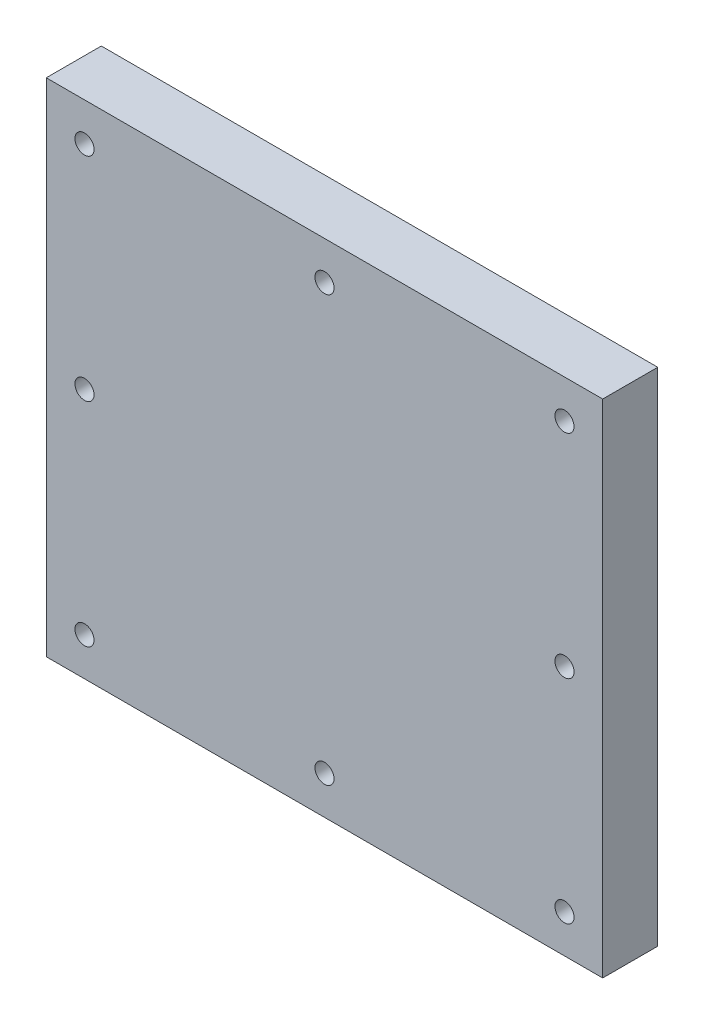
SolidWorks part; units mm, degrees
ref_plane "Front Plane" through (0, 0, 0) normal (0, 0, 1) x (1, 0, 0)
ref_plane "Top Plane" through (0, 0, 0) normal (0, 1, 0) x (1, 0, 0)
ref_plane "Right Plane" through (0, 0, 0) normal (1, 0, 0) x (0, 0, -1)
sketch "Sketch1" plane through (0, 0, 0) normal (0, 0, 1) x (1, 0, 0)
  line L1 (254.6449, 234.2275) -> (439.5569, 234.2275)
  line L2 (254.6449, 234.2275) -> (254.6449, 67.6035)
  line L3 (254.6449, 67.6035) -> (439.5569, 67.6035)
  line L4 (439.5569, 234.2275) -> (439.5569, 67.6035)
  dimension "D1" = 184.912
  dimension "D2" = 166.624
extrude "Boss-Extrude1" add sketch "Sketch1" along normal blind 18.288
sketch "Sketch3" plane through (0, 0, 18.288) normal (0, 0, 1) x (1, 0, 0)
  circle A0 centre (267.3449, 221.5275) radius 3.175
  circle A1 centre (347.1009, 221.5275) radius 3.175
  circle A2 centre (426.8569, 221.5275) radius 3.175
  circle A3 centre (426.8569, 150.9155) radius 3.175
  circle A4 centre (267.3449, 150.9155) radius 3.175
  circle A5 centre (347.1009, 80.3035) radius 3.175
  circle A6 centre (426.8569, 80.3035) radius 3.175
  circle A7 centre (267.3449, 80.3035) radius 3.175
extrude "Cut-Extrude2" cut sketch "Sketch3" against normal blind 25.4
